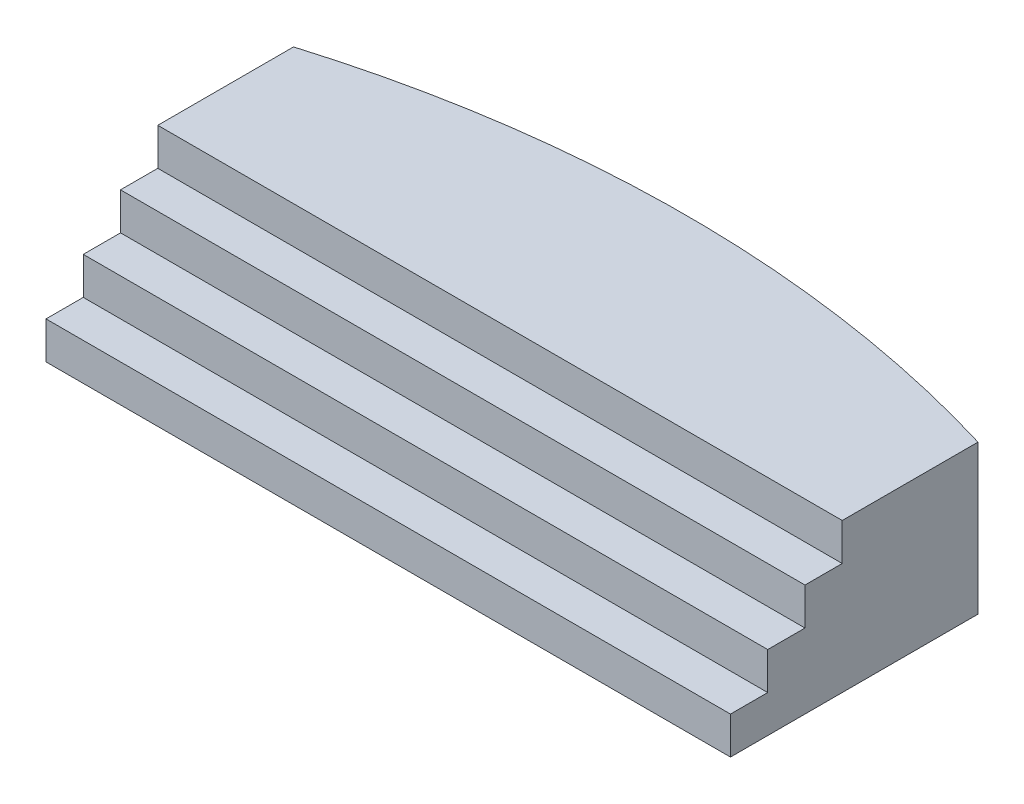
SolidWorks part; units mm, degrees
material "Alloy Steel"
ref_plane "Front Plane" through (0, 0, 0) normal (0, 0, 1) x (1, 0, 0)
ref_plane "Top Plane" through (0, 0, 0) normal (0, 1, 0) x (1, 0, 0)
ref_plane "Right Plane" through (0, 0, 0) normal (1, 0, 0) x (0, 0, -1)
sketch "Sketch2" plane through (0, 0, 0) normal (0, 1, 0) x (1, 0, 0)
  circle A0 centre (0, 0) radius 7945.75
  dimension "D1" = 15891.5
extrude "Boss-Extrude1" add sketch "Sketch2" along normal blind 1000
sketch "Sketch3" plane through (0, 1000, 0) normal (0, 1, 0) x (1, 0, 0)
  line L1 (-2296.3939, 9945.75) -> (2296.3939, 9945.75)
  line L2 (-2296.3939, 9945.75) -> (-2296.3939, 5945.75)
  line L3 (-2296.3939, 5945.75) -> (2296.3939, 5945.75)
  line L4 (2296.3939, 9945.75) -> (2296.3939, 5945.75)
  line L5 (-2296.3939, 9945.75) -> (2296.3939, 5945.75) construction
  line L6 (-2296.3939, 5945.75) -> (2296.3939, 9945.75) construction
  circle A0 centre (0, 0) radius 7945.75 construction
  point P0 (0, 7945.75)
  dimension "D1" = 4592.7878
  dimension "D2" = 4000
extrude "Cut-Extrude1" cut sketch "Sketch3" against normal blind 1000 flip side to cut
sketch "Sketch4" plane through (2296.3939, 0, 0) normal (1, 0, 0) x (0, 0, -1)
  line L1 (5945.75, 0) -> (5945.75, 1000) construction
  line L2 (5945.75, 250) -> (6195.75, 250)
  line L3 (6195.75, 250) -> (6195.75, 500)
  line L4 (6195.75, 500) -> (6445.75, 500)
  line L5 (6445.75, 500) -> (6445.75, 750)
  line L6 (6445.75, 750) -> (6695.75, 750)
  line L7 (6695.75, 750) -> (6695.75, 1000)
  line L8 (5945.75, 1000) -> (7606.6759, 1000) construction
  line L9 (6695.75, 1000) -> (5945.75, 1000)
  line L10 (5945.75, 1000) -> (5945.75, 250)
  dimension "D2" = 250
  dimension "D3" = 250
  dimension "D4" = 250
  dimension "D5" = 250
  dimension "D6" = 250
extrude "Cut-Extrude2" cut sketch "Sketch4" against normal blind 5000
